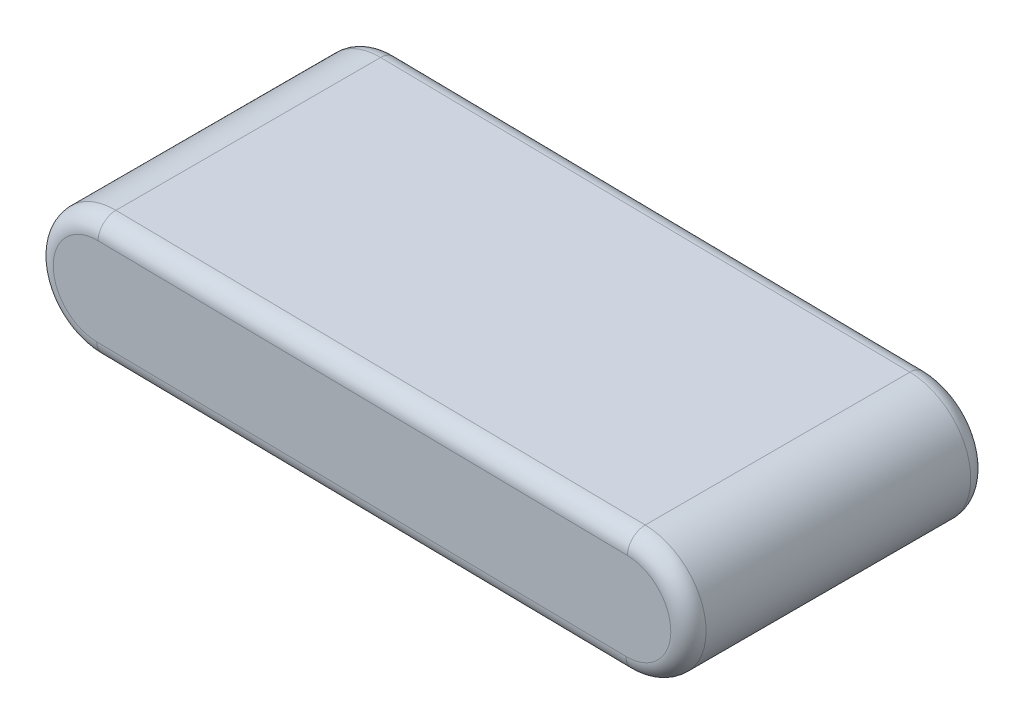
SolidWorks part; units mm, degrees
ref_plane "Plano frontal" through (0, 0, 0) normal (0, 0, 1) x (1, 0, 0)
ref_plane "Plano superior" through (0, 0, 0) normal (0, 1, 0) x (1, 0, 0)
ref_plane "Plano direito" through (0, 0, 0) normal (1, 0, 0) x (0, 0, -1)
sketch "Esboço1" plane through (0, 0, 0) normal (0, 0, 1) x (1, 0, 0)
  line L0 (-15, 0.2234) -> (15, -0.2234) construction
  line L1 (-15, 0.2234) -> (15, -0.2234) construction
  line L2 (-14.9479, 3.723) -> (15.0521, 3.2762)
  line L3 (-15.0521, -3.2762) -> (14.9479, -3.723)
  arc A0 (-14.9479, 3.723) -> (-15.0521, -3.2762) centre (-15, 0.2234) ccw
  arc A1 (14.9479, -3.723) -> (15.0521, 3.2762) centre (15, -0.2234) ccw
  point P0 (0, 0)
  dimension "D2" = 3.5
  dimension "D1" = 30
extrude "Ressalto-extrusão1" add sketch "Esboço1" along normal blind 17
fillet "Filete1" radius 1 8 edges at (18.4996, -0.2756, 0) (-0.0521, -3.4996, 0) (-18.4996, 0.2756, 0) (18.4996, -0.2756, 17) (-0.0521, -3.4996, 17) (-18.4996, 0.2756, 17) (0.0521, 3.4996, 0) (0.0521, 3.4996, 17)
